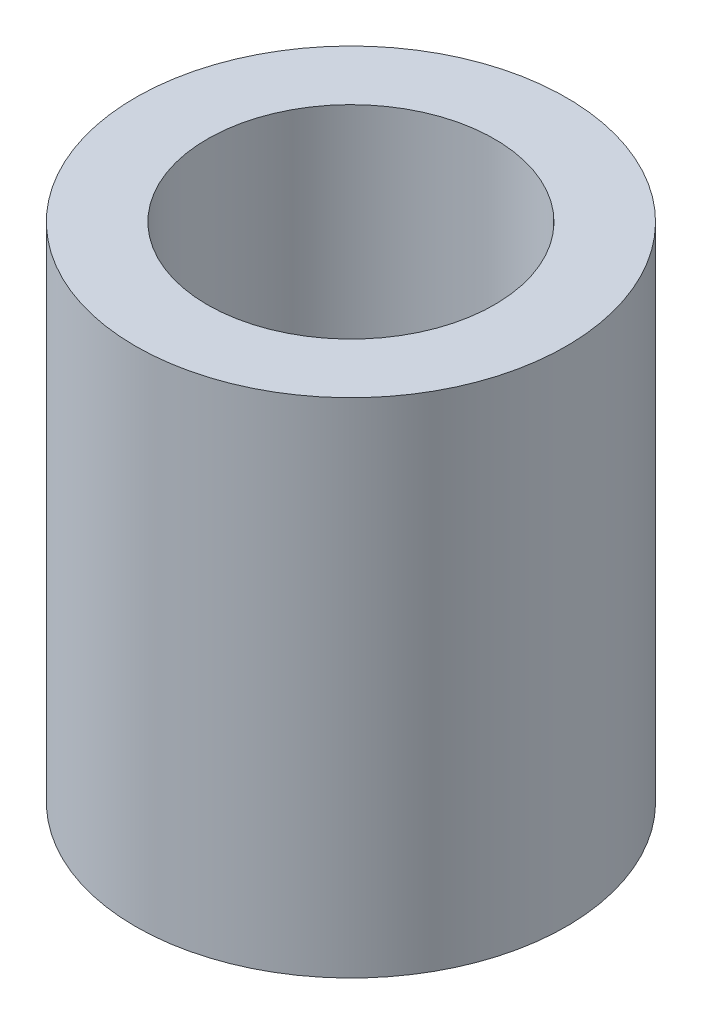
SolidWorks part; units mm, degrees
ref_plane "Спереди" through (0, 0, 0) normal (0, 0, 1) x (1, 0, 0)
ref_plane "Сверху" through (0, 0, 0) normal (0, 1, 0) x (1, 0, 0)
ref_plane "Справа" through (0, 0, 0) normal (1, 0, 0) x (0, 0, -1)
sketch "Эскиз1" plane through (0, 0, 0) normal (0, 1, 0) x (1, 0, 0)
  circle A0 centre (0, 0) radius 2
  circle A1 centre (0, 0) radius 3
  dimension "D1" = 4
  dimension "D2" = 6
extrude "Бобышка-Вытянуть1" add sketch "Эскиз1" along normal blind 7
